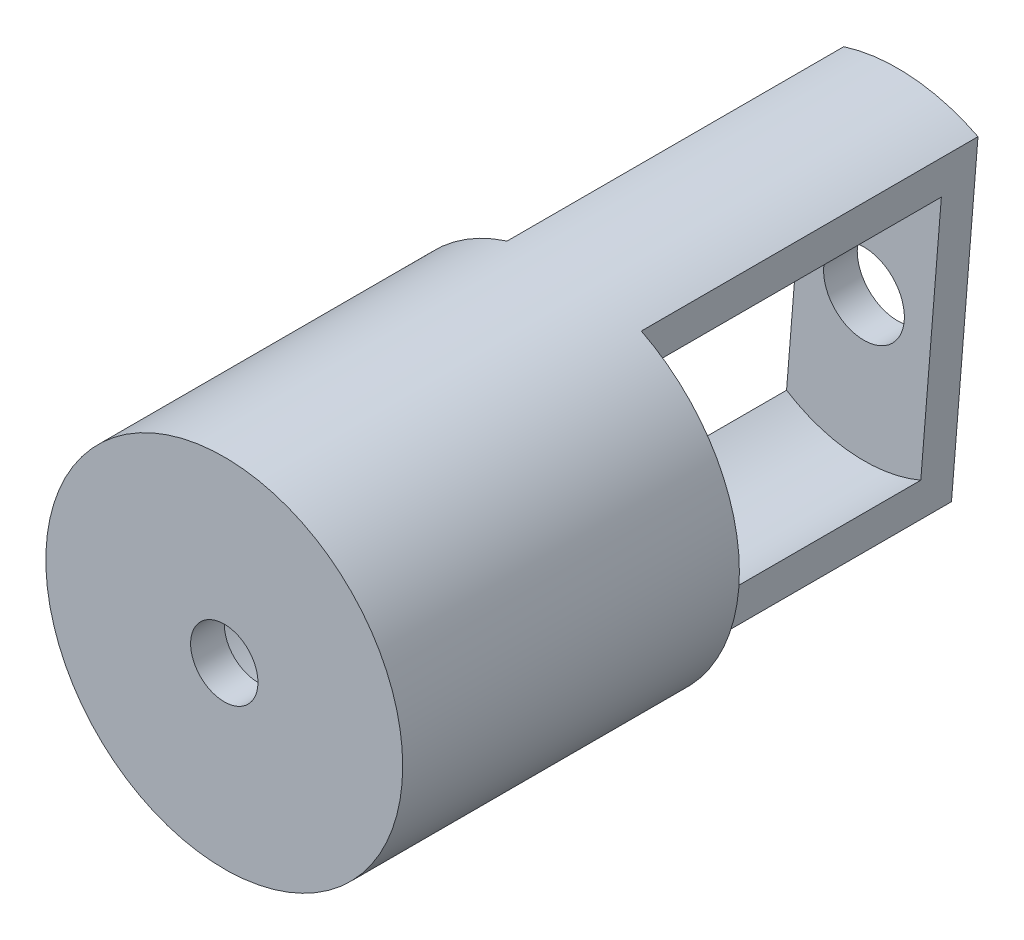
SolidWorks part; units mm, degrees
ref_plane "Front Plane" through (0, 0, 0) normal (0, 0, 1) x (1, 0, 0)
ref_plane "Top Plane" through (0, 0, 0) normal (0, 1, 0) x (1, 0, 0)
ref_plane "Right Plane" through (0, 0, 0) normal (1, 0, 0) x (0, 0, -1)
sketch "Sketch1" plane through (0, 0, 0) normal (0, 0, 1) x (1, 0, 0)
  circle A0 centre (0, 0) radius 21.5
  circle A1 centre (0, 0) radius 5
  dimension "D1" = 43
extrude "Boss-Extrude1" add sketch "Sketch1" along normal blind 5
sketch "Sketch2" plane through (0, 0, 5) normal (0, 0, 1) x (1, 0, 0)
  circle A0 centre (0, 0) radius 21.5
extrude "Extrude-Thin1" add sketch "Sketch2" against normal blind 100 thin
sketch "Sketch3" plane through (0, 0, -95) normal (0, 0, -1) x (-1, 0, 0)
  line L0 (11.9367, -23.6593) -> (11.4948, -18.1692)
  line L2 (8.4407, 19.7738) -> (7.9988, 25.264)
  line L3 (-11.4948, 18.1692) -> (-11.9367, 23.6593)
  line L4 (-7.9988, -25.264) -> (-8.4407, -19.7738)
  arc A0 (11.4948, -18.1692) -> (8.4407, 19.7738) centre (0, 0) ccw
  arc A1 (11.9367, -23.6593) -> (7.9988, 25.264) centre (0, 0) ccw
  arc A2 (-11.4948, 18.1692) -> (-8.4407, -19.7738) centre (0, 0) ccw
  arc A3 (-11.9367, 23.6593) -> (-7.9988, -25.264) centre (0, 0) ccw
extrude "Cut-Extrude1" cut sketch "Sketch3" against normal blind 50
sketch "Sketch4" plane through (0, 0, -95) normal (0, 0, -1) x (-1, 0, 0)
  line L0 (-7.9988, -25.264) -> (-11.9367, 23.6593)
  line L1 (11.9367, -23.6593) -> (7.9988, 25.264)
  arc A0 (-8.4407, -19.7738) -> (11.4948, -18.1692) centre (0, 0) ccw
  arc A1 (-7.9988, -25.264) -> (11.9367, -23.6593) centre (0, 0) ccw
  arc A2 (7.9988, 25.264) -> (-11.9367, 23.6593) centre (0, 0) ccw
  arc A3 (8.4407, 19.7738) -> (-11.4948, 18.1692) centre (0, 0) ccw
  arc M1 (11.4948, -18.1692) -> (-8.4407, -19.7738) centre (0, 0) cw
extrude "Boss-Extrude2" add sketch "Sketch4" against normal blind 5 contours L1 A3 L0 M1
sketch "Sketch5" plane through (0, 0, -95) normal (0, 0, -1) x (-1, 0, 0)
  circle A0 centre (0, 0) radius 6
extrude "Cut-Extrude2" cut sketch "Sketch5" against normal blind 5
